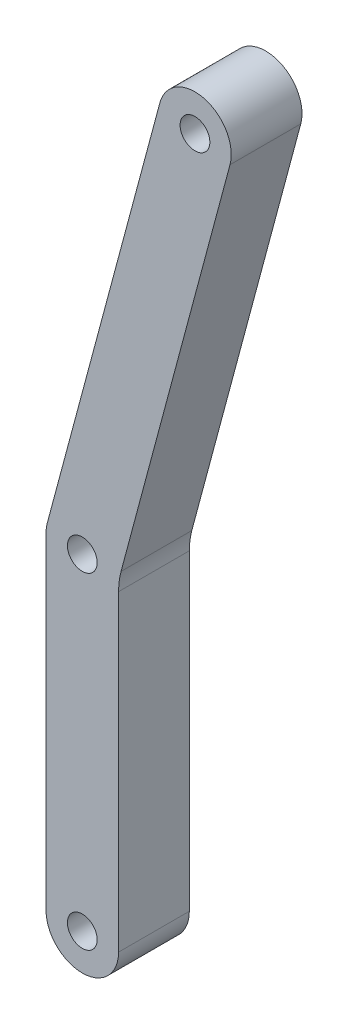
SolidWorks part; units mm, degrees
ref_plane "Plan de face" through (0, 0, 0) normal (0, 0, 1) x (1, 0, 0)
ref_plane "Plan de dessus" through (0, 0, 0) normal (0, 1, 0) x (1, 0, 0)
ref_plane "Plan de droite" through (0, 0, 0) normal (1, 0, 0) x (0, 0, -1)
sketch "Esquisse1" plane through (0, 0, 0) normal (0, 0, 1) x (1, 0, 0)
  line L0 (0, 0) -> (0, 45) construction
  line L1 (-5, 0) -> (-5, 45)
  line L2 (5, 0) -> (5, 45)
  line L3 (0, 45) -> (15.5291, 102.9555) construction
  line L4 (-4.8296, 46.2941) -> (10.6995, 104.2496)
  line L5 (4.8296, 43.7059) -> (20.3588, 101.6615)
  arc A0 (-5, 0) -> (5, 0) centre (0, 0) ccw
  arc A1 (5, 45) -> (-5, 45) centre (0, 45) ccw
  arc A2 (-4.8296, 46.2941) -> (4.8296, 43.7059) centre (0, 45) ccw
  arc A3 (20.3588, 101.6615) -> (10.6995, 104.2496) centre (15.5291, 102.9555) ccw
  circle A4 centre (0, 0) radius 2.05
  circle A5 centre (0, 45) radius 2.05
  circle A6 centre (15.5291, 102.9555) radius 2.05
  point P3 (0, 22.5)
  point P8 (7.7646, 73.9778)
  dimension "D5" = 4.1
  dimension "D6" = 4.1
  dimension "D7" = 4.1
  dimension "D1" = 60
  dimension "D2" = 45
  dimension "D3" = 165
  dimension "D4" = 10
extrude "Boss.-Extru.1" add sketch "Esquisse1" along normal blind 9.75 contours L5 A3 L4 A1 L2 A6 | A1 A2 L5 L2 A5 | A2 L1 A0 L2 L5 A4
fillet "Congé1" radius 10 1 edges at (5, 44.3417, 4.875)
